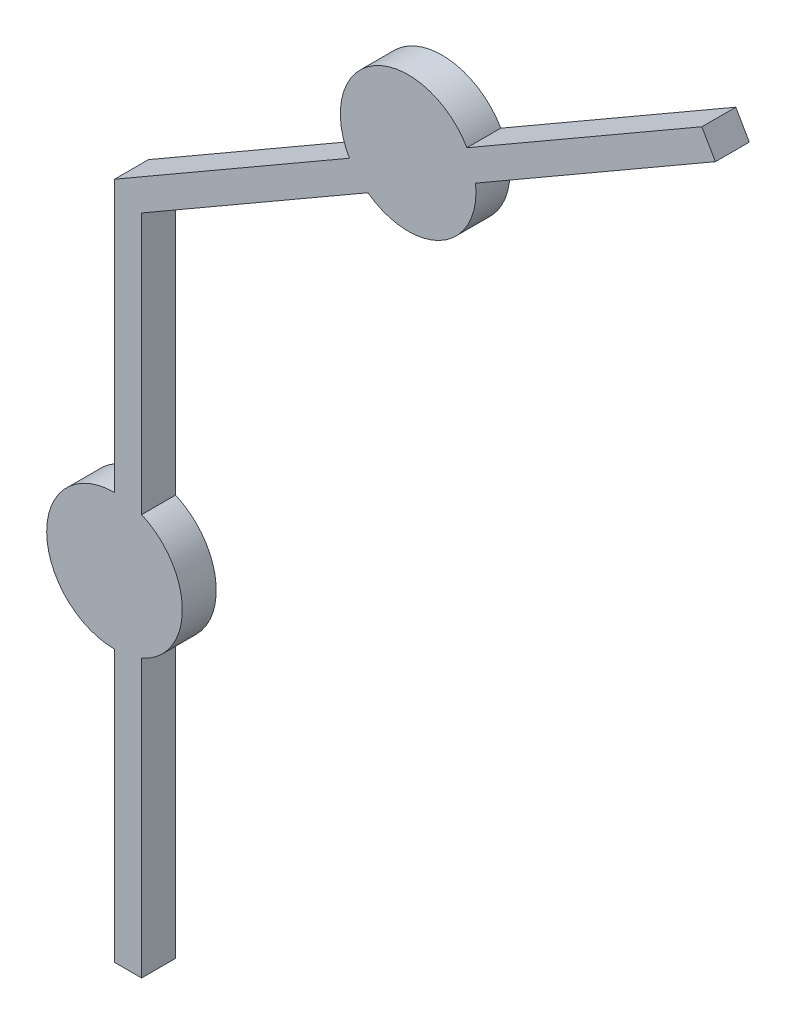
SolidWorks part; units mm, degrees
ref_plane "Front Plane" through (0, 0, 0) normal (0, 0, 1) x (1, 0, 0)
ref_plane "Top Plane" through (0, 0, 0) normal (0, 1, 0) x (1, 0, 0)
ref_plane "Right Plane" through (0, 0, 0) normal (1, 0, 0) x (0, 0, -1)
sketch "Sketch1" plane through (0, 0, 0) normal (0, 0, 1) x (1, 0, 0)
  line L0 (0, 0) -> (0, 30)
  line L1 (0, 30) -> (25.9808, 45)
  dimension "D1" = 120
  dimension "D2" = 30
extrude "Extrude-Thin1" add sketch "Sketch1" along normal blind 1.5 thin
sketch "Sketch2" plane through (0, 0, 0) normal (0, 0, 1) x (1, 0, 0)
  line L1 (0, 30) -> (25.9808, 45) construction
  line L2 (0, 0) -> (0, 30) construction
  circle A0 centre (12.9904, 37.5) radius 3
  circle A1 centre (0, 15) radius 3
  point P4 (0, 0)
  point P7 (12.9904, 37.5)
  point P8 (0, 0)
  point P11 (0, 15)
  dimension "D1" = 6
extrude "Boss-Extrude1" add sketch "Sketch2" along normal up to surface (1.5 mm away) up to face at (9.1603, 24.7113, 1.5)
equation "\"SideLenght\"= 30"
equation "\"Tickness\" = 1.5"
equation "\"Connector\"= 6"
equation "\"ConnectorPin\"= 3"
equation "\"LineWidth\"= 1.2"
equation "\"D2@Sketch1\"=\"SideLenght\""
equation "\"D5@Extrude-Thin1\"=\"LineWidth\""
equation "\"D1@Extrude-Thin1\"=\"Tickness\""
equation "\"D1@Sketch2\"=\"Connector\""
